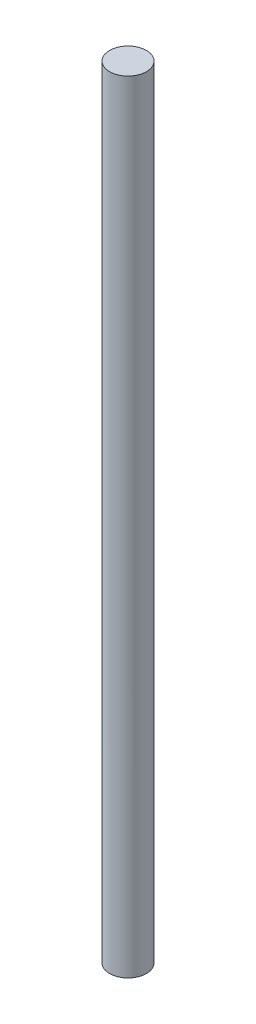
SolidWorks part; units mm, degrees
material "AISI 4340 Steel, annealed"
ref_plane "X-Y Datum" through (0, 0, 0) normal (0, 0, 1) x (1, 0, 0)
ref_plane "X-Z Datum" through (0, 0, 0) normal (0, 1, 0) x (1, 0, 0)
ref_plane "Y-Z Datum" through (0, 0, 0) normal (1, 0, 0) x (0, 0, -1)
ref_plane "Plane1" through (0, 159.9626, 0) normal (0, 1, 0) x (1, 0, 0)
sketch "Sketch2" plane through (0, 159.9626, 0) normal (0, 1, 0) x (1, 0, 0)
  circle A0 centre (0, 0) radius 6.35
  circle A1 centre (0, 0) radius 5.6134
  dimension "D1" = 11.2268
  dimension "D2" = 12.7
extrude "Boss-Extrude2" add sketch "Sketch2" along normal up to surface (134.5626 mm away) and the other way up to surface (134.5626 mm away) contours A0
